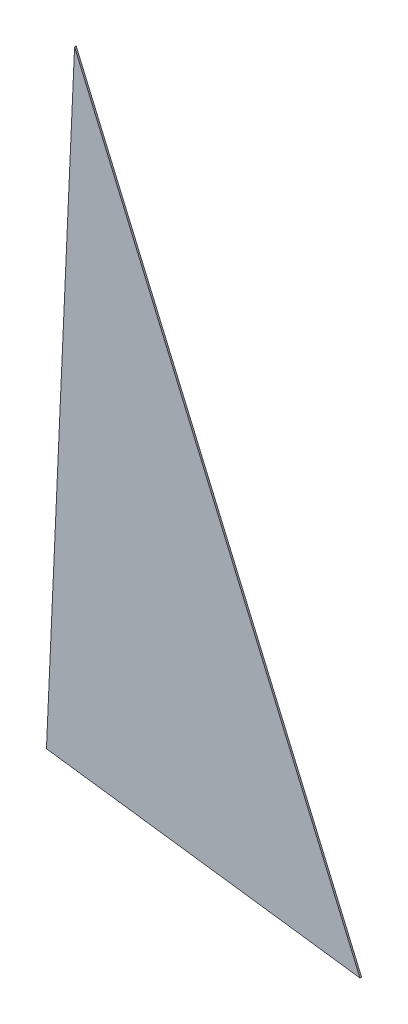
SolidWorks part; units mm, degrees
ref_plane "Front Plane" through (0, 0, 0) normal (0, 0, 1) x (1, 0, 0)
ref_plane "Top Plane" through (0, 0, 0) normal (0, 1, 0) x (1, 0, 0)
ref_plane "Right Plane" through (0, 0, 0) normal (1, 0, 0) x (0, 0, -1)
sketch "Sketch2" plane through (0, 0, 0) normal (0, 0, 1) x (1, 0, 0)
  line L0 (90.1102, 286.9546) -> (356.7294, -333.0454)
  line L1 (356.7294, -333.0454) -> (56.2083, -462.2787)
  line L2 (56.2083, -462.2787) -> (90.1102, 286.9546)
  dimension "D1" = 620
  dimension "D2" = 25.86
extrude "Boss-Extrude3" add sketch "Sketch2" along normal blind 1.5
sketch "Sketch3" plane through (0, 0, 0) normal (0, 0, -1) x (-1, 0, 0)
  line L0 (-356.7294, -333.0454) -> (-63.8222, -294.0111)
  line L1 (-90.1102, 286.9546) -> (-56.2083, -462.2787) construction
  line L2 (-63.8222, -294.0111) -> (-56.2083, -462.2787)
  line L3 (-56.2083, -462.2787) -> (-356.7294, -333.0454)
  dimension "D1" = 85
extrude "Cut-Extrude1" cut sketch "Sketch3" against normal blind 10
